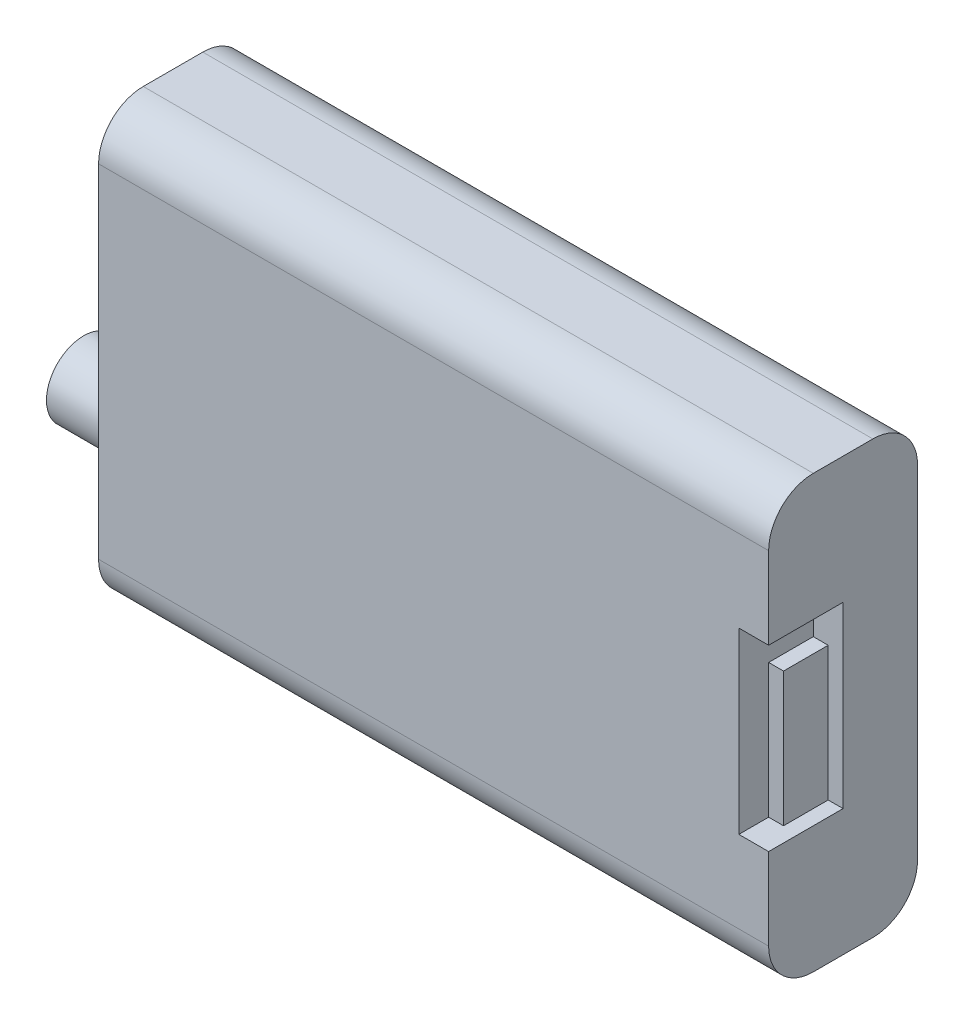
SolidWorks part; units mm, degrees
ref_plane "Front Plane" through (0, 0, 0) normal (0, 0, 1) x (1, 0, 0)
ref_plane "Top Plane" through (0, 0, 0) normal (0, 1, 0) x (1, 0, 0)
ref_plane "Right Plane" through (0, 0, 0) normal (1, 0, 0) x (0, 0, -1)
sketch "Sketch1" plane through (0, 0, 0) normal (0, 0, 1) x (1, 0, 0)
  line L1 (-22.5, -14.5) -> (22.5, -14.5)
  line L2 (-22.5, -14.5) -> (-22.5, 14.5)
  line L3 (-22.5, 14.5) -> (22.5, 14.5)
  line L4 (22.5, -14.5) -> (22.5, 14.5)
  point P0 (0, 0)
  dimension "D1" = 45
  dimension "D2" = 29
extrude "Boss-Extrude1" add sketch "Sketch1" along normal blind 10
sketch "Sketch2" plane through (0, 0, 10) normal (0, 0, 1) x (1, 0, 0)
  line L1 (22.5, -14.5) -> (22.5, 14.5) construction
  line L2 (22.5, -6) -> (20.5, -6)
  line L3 (22.5, -6) -> (22.5, 6)
  line L4 (22.5, 6) -> (20.5, 6)
  line L5 (20.5, -6) -> (20.5, 6)
  dimension "D1" = 12
  dimension "D2" = 2
extrude "Cut-Extrude1" cut sketch "Sketch2" against normal blind 5
sketch "Sketch3" plane through (20.5, 0, 0) normal (1, 0, 0) x (0, 0, -1)
  line L0 (-5, -6) -> (-10, -6) construction
  line L1 (-8, -6) -> (-5, -6)
  line L2 (-8, -6) -> (-8, 3)
  line L3 (-8, 3) -> (-5, 3)
  line L4 (-5, -6) -> (-5, 3)
  line L5 (-5, 6) -> (-5, -6) construction
  dimension "D1" = 9
  dimension "D2" = 3
extrude "Boss-Extrude2" add sketch "Sketch3" along normal blind 1
sketch "Sketch4" plane through (-22.5, 0, 0) normal (-1, 0, 0) x (0, 0, 1)
  circle A0 centre (5, -6.5) radius 2.5
  dimension "D2" = 5
extrude "Boss-Extrude3" add sketch "Sketch4" along normal blind 6
sketch "Sketch5" plane through (-28.5, 0, 0) normal (-1, 0, 0) x (0, 0, 1)
  circle A0 centre (5, -6.5) radius 1.85
  dimension "D1" = 3.7
extrude "Cut-Extrude2" cut sketch "Sketch5" against normal blind 4
sketch "Sketch6" plane through (-24.5, 0, 0) normal (-1, 0, 0) x (0, 0, 1)
  circle A0 centre (5, -6.5) radius 0.275
  dimension "D1" = 0.55
extrude "Boss-Extrude4" add sketch "Sketch6" along normal blind 4
fillet "Fillet2" radius 3 1 edges at (0, 14.5, 0)
fillet "Fillet3" radius 3 1 edges at (0, 14.5, 10)
fillet "Fillet4" radius 3 1 edges at (0, -14.5, 0)
fillet "Fillet5" radius 3 1 edges at (0, -14.5, 10)
